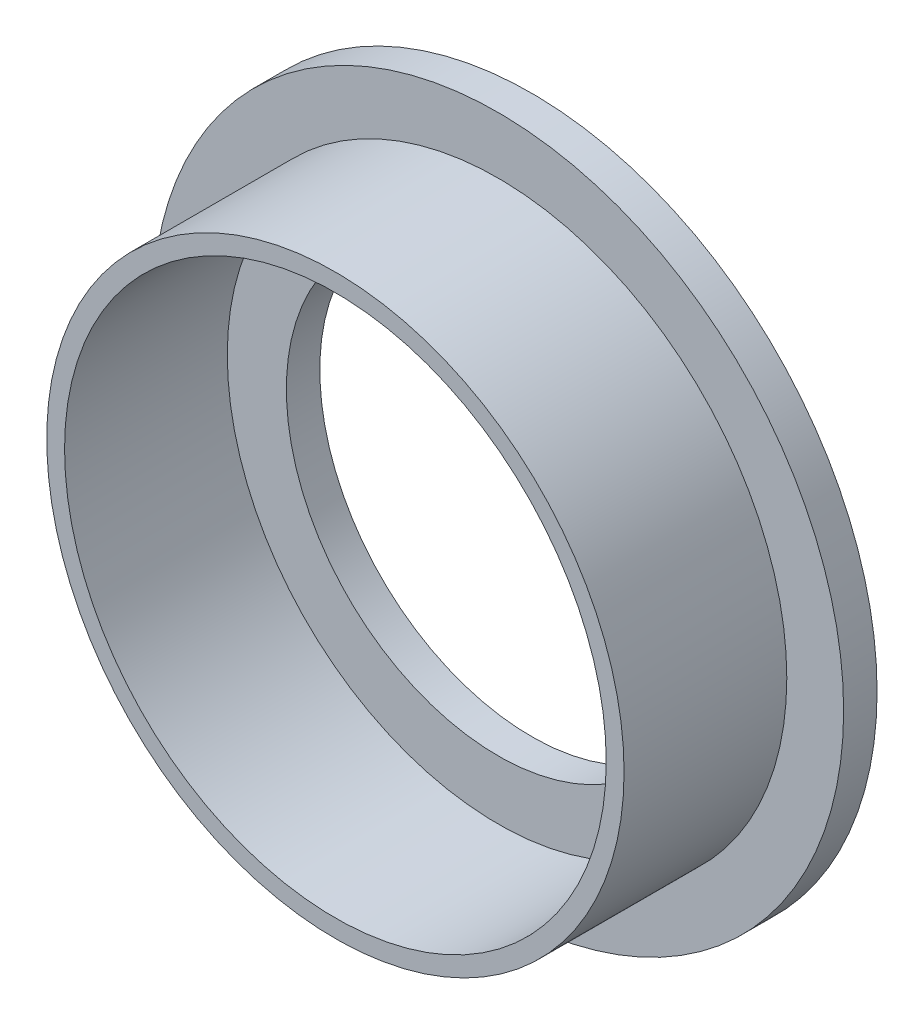
SolidWorks part; units mm, degrees
ref_plane "Alzado" through (0, 0, 0) normal (0, 0, 1) x (1, 0, 0)
ref_plane "Planta" through (0, 0, 0) normal (0, 1, 0) x (1, 0, 0)
ref_plane "Vista lateral" through (0, 0, 0) normal (1, 0, 0) x (0, 0, -1)
sketch "Croquis3" plane through (0, 0, 0) normal (0, 0, 1) x (1, 0, 0)
  line L0 (0, 0) -> (38, 0) construction
  circle A0 centre (38, 0) radius 9.5
  circle A1 centre (38, 0) radius 15.5
  dimension "D1" = 19
  dimension "D2" = 31
  dimension "D3" = 38
extrude "Saliente-Extruir3" add sketch "Croquis3" along normal blind 1.5 separate body
sketch "Croquis4" plane through (0, 0, 1.5) normal (0, 0, 1) x (1, 0, 0)
  circle A0 centre (38, 0) radius 12.15
  circle A1 centre (38, 0) radius 12.95
  dimension "D1" = 24.3
  dimension "D2" = 25.9
extrude "Saliente-Extruir4" add sketch "Croquis4" along normal blind 7.3
